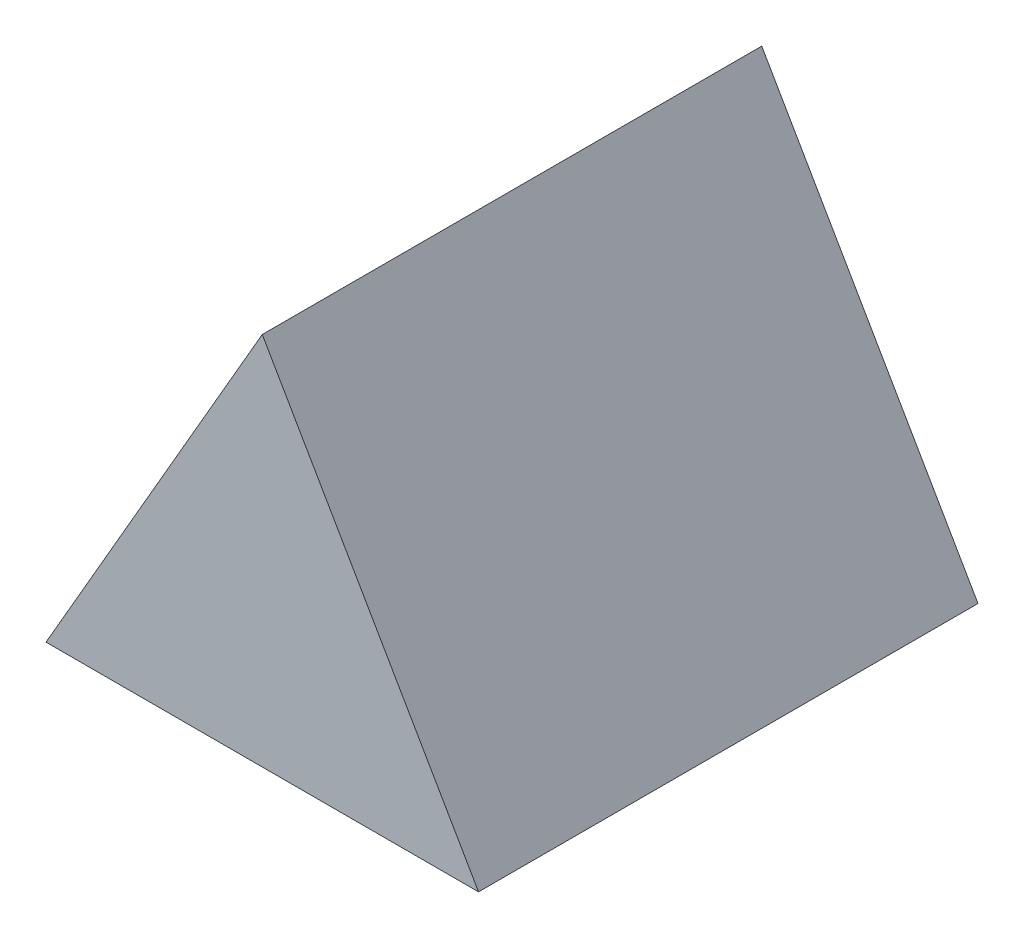
SolidWorks part; units mm, degrees
ref_plane "Front Plane" through (0, 0, 0) normal (0, 0, 1) x (1, 0, 0)
ref_plane "Top Plane" through (0, 0, 0) normal (0, 1, 0) x (1, 0, 0)
ref_plane "Right Plane" through (0, 0, 0) normal (1, 0, 0) x (0, 0, -1)
sketch "Sketch1" plane through (0, 0, 0) normal (0, 0, 1) x (1, 0, 0)
  line L0 (0, 30) -> (-25.9808, -15)
  line L1 (-25.9808, -15) -> (25.9808, -15)
  line L2 (25.9808, -15) -> (0, 30)
extrude "Prism" add sketch "Sketch1" along normal blind 60
